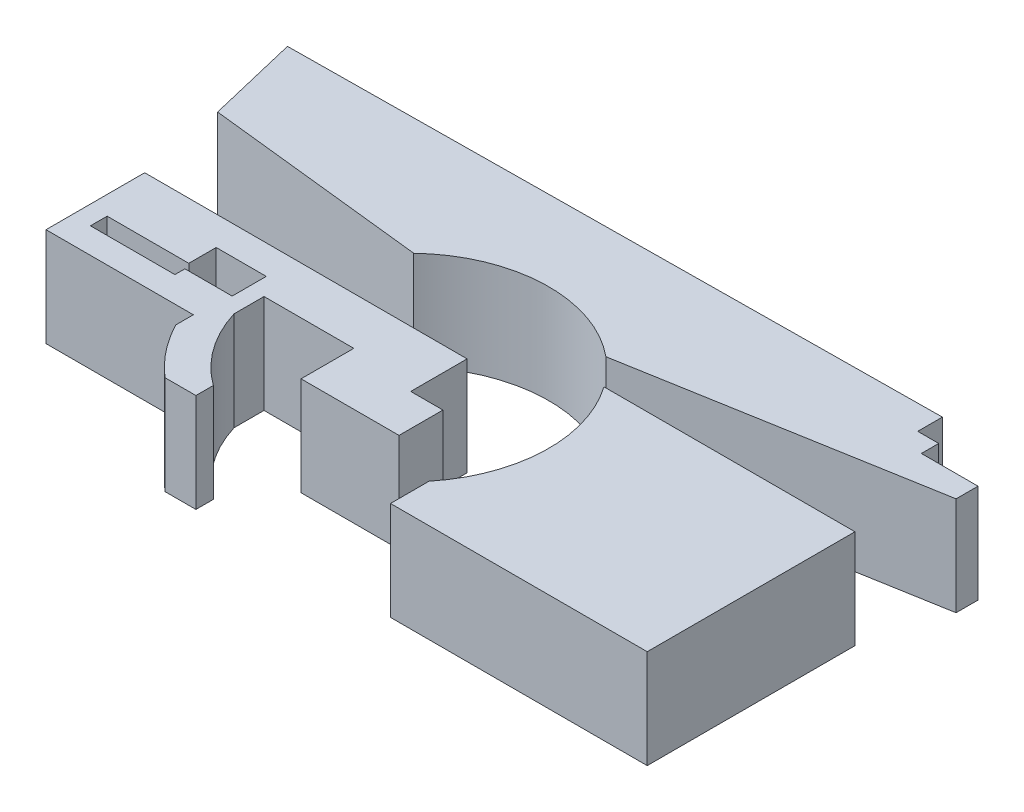
SolidWorks part; units mm, degrees
ref_plane "前视基准面" through (0, 0, 0) normal (0, 0, 1) x (1, 0, 0)
ref_plane "上视基准面" through (0, 0, 0) normal (0, 1, 0) x (1, 0, 0)
ref_plane "右视基准面" through (0, 0, 0) normal (1, 0, 0) x (0, 0, -1)
sketch "草图1" plane through (0, 0, 0) normal (0, 1, 0) x (1, 0, 0)
  line L0 (-148.2705, 71.2161) -> (-148.2705, -58.7839) construction
  line L1 (-148.2705, -58.7839) -> (91.7295, -58.7839) construction
  line L2 (91.7295, -58.7839) -> (91.7295, 71.2161) construction
  line L3 (91.7295, 71.2161) -> (-148.2705, 71.2161) construction
  line L4 (-136.0829, 54.969) -> (61.0557, 56.9126)
  line L5 (61.0557, 56.9126) -> (61.0557, 49.4158)
  line L6 (61.0557, 49.4158) -> (67.4419, 49.4158)
  line L7 (67.4419, 49.4158) -> (67.4419, 44.1403)
  line L8 (67.4419, 44.1403) -> (84.6568, 44.1403)
  line L9 (84.6568, 44.1403) -> (84.6568, 37.4764)
  line L10 (84.6568, 37.4764) -> (-5.981, 21.6675)
  line L11 (-62.4268, 19.697) -> (-129.4191, 27.0642)
  line L12 (-129.4191, 27.0642) -> (-136.0829, 54.969)
  line L13 (-102.032, 0) -> (-26.5085, 0)
  line L14 (-124.5224, 0) -> (-102.032, 0)
  line L15 (-124.5224, 0) -> (-124.5224, -29.999)
  line L16 (-124.5224, -29.999) -> (-102.032, -29.999)
  line L18 (-26.5085, 0) -> (-26.5085, -17.1429)
  line L19 (-26.5085, -17.1429) -> (-16.7131, -17.1429)
  line L20 (-16.7131, -17.1429) -> (-16.7131, -30.4908)
  line L21 (-16.7131, -30.4908) -> (-46.5, -30.4908)
  line L22 (-46.5, -30.4908) -> (-46.5, -14.4501)
  line L23 (-46.5, -14.4501) -> (-73.7919, -14.4501)
  line L24 (-73.7919, -14.4501) -> (-73.7919, -23.5635)
  line L26 (-58.082, -45.5777) -> (-58.082, -50.8691)
  line L27 (-58.082, -50.8691) -> (-67.4881, -50.8691)
  line L28 (-79.7266, -35.3675) -> (-79.7266, -29.999)
  line L29 (-79.7266, -29.999) -> (-102.032, -29.999)
  line L30 (-118.7899, -17.1429) -> (-93.9743, -17.1429)
  line L31 (-93.9743, -17.1429) -> (-93.9743, -8.8126)
  line L32 (-93.9743, -8.8126) -> (-78.75, -8.8126)
  line L33 (-78.75, -8.8126) -> (-78.75, -19.1831)
  line L34 (-78.75, -19.1831) -> (-93.1126, -19.1831)
  line L35 (-93.1126, -19.1831) -> (-93.1126, -22.2246)
  line L36 (-93.1126, -22.2246) -> (-118.7899, -22.2246)
  line L37 (-118.7899, -22.2246) -> (-118.7899, -17.1429)
  line L39 (1.6517, 13.4378) -> (77.9559, 13.4378)
  line L40 (-0.0847, -37.9904) -> (-0.0847, -49.7129)
  line L41 (-0.0847, -49.7129) -> (77.9559, -49.7129)
  line L42 (77.9559, 13.4378) -> (77.9559, -49.7129)
  arc A0 (-73.7919, -23.5635) -> (-58.082, -45.5777) centre (-33.0933, -11.1324) ccw
  arc A1 (-0.0847, -37.9904) -> (1.6517, 13.4378) centre (-33.0933, -11.1324) ccw
  arc A2 (-79.7266, -35.3675) -> (-67.4881, -50.8691) centre (-33.0933, -11.1324) ccw
  arc A3 (-83.3557, -26.4847) -> (-63.9542, -53.672) centre (-33.0933, -11.1324) ccw construction
  arc A4 (-5.981, 21.6675) -> (-62.4268, 19.697) centre (-33.0933, -11.1324) ccw
  dimension "D1" = 240
  dimension "D2" = 130
  dimension "D3" = 10
extrude "凸台-拉伸1" add sketch "草图1" along normal blind 30
